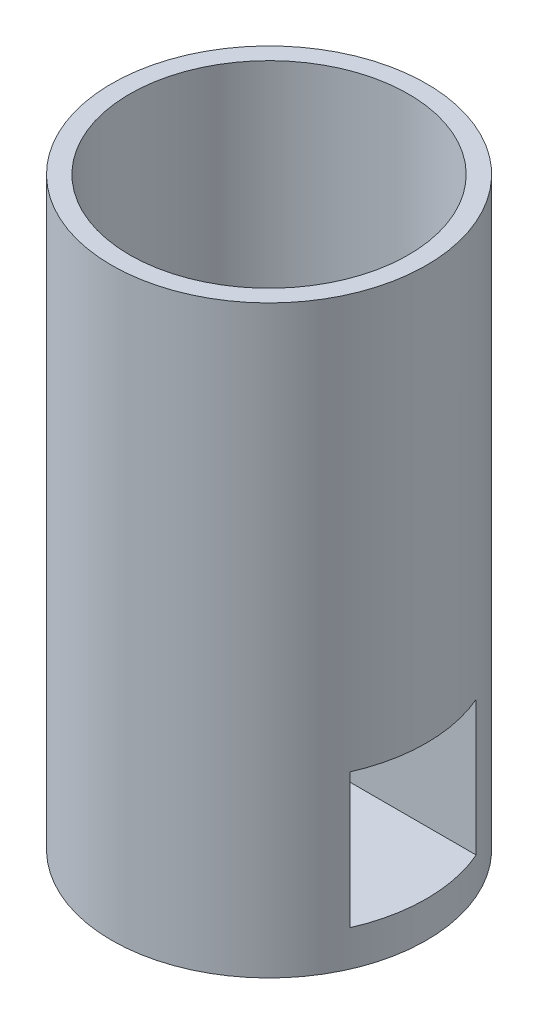
SolidWorks part; units mm, degrees
ref_plane "Front Plane" through (0, 0, 0) normal (0, 0, 1) x (1, 0, 0)
ref_plane "Top Plane" through (0, 0, 0) normal (0, 1, 0) x (1, 0, 0)
ref_plane "Right Plane" through (0, 0, 0) normal (1, 0, 0) x (0, 0, -1)
sketch "Sketch1" plane through (0, 0, 0) normal (0, 1, 0) x (1, 0, 0)
  line L1 (-9.2182, 6.0273) -> (15.7818, 6.0273)
  line L2 (-9.2182, 6.0273) -> (-9.2182, -9.9727)
  line L3 (-9.2182, -9.9727) -> (15.7818, -9.9727)
  line L4 (15.7818, 6.0273) -> (15.7818, -9.9727)
  dimension "D1" = 16
  dimension "D2" = 25
extrude "Boss-Extrude1" add sketch "Sketch1" along normal blind 20
sketch "Sketch6" plane through (0, 0, 0) normal (0, 1, 0) x (1, 0, 0)
  circle A0 centre (3.8725, -1.9531) radius 17.5
extrude "Boss-Extrude4" add sketch "Sketch6" along normal blind 65
sketch "Sketch2" plane through (-9.2182, 0, 0) normal (-1, 0, 0) x (0, 0, 1)
  line L0 (-6.0273, 20) -> (-6.0273, 0) construction
  line L1 (-5.0273, 19) -> (8.9727, 19)
  line L2 (-5.0273, 19) -> (-5.0273, 4)
  line L3 (-5.0273, 4) -> (8.9727, 4)
  line L4 (8.9727, 19) -> (8.9727, 4)
  line L5 (9.9727, 20) -> (9.9727, 0) construction
  line L6 (-6.0273, 20) -> (9.9727, 20) construction
  dimension "D1" = 1
  dimension "D2" = 1
  dimension "D3" = 1
  dimension "D4" = 15
extrude "Cut-Extrude1" cut sketch "Sketch2" against normal blind 40 and the other way blind 65
sketch "Sketch3" plane through (0, 0, 0) normal (0, -1, 0) x (-1, 0, 0)
  line L0 (-15.7818, -9.9727) -> (-15.7818, 6.0273) construction
  line L1 (9.2182, -9.9727) -> (-15.7818, -9.9727) construction
  line L2 (-15.7818, 6.0273) -> (9.2182, 6.0273) construction
  circle A0 centre (-9.7818, -1.9727) radius 1
  circle A1 centre (0.2182, -1.9727) radius 1
  dimension "D6" = 2
  dimension "D7" = 2
  dimension "D1" = 6
  dimension "D2" = 16
  dimension "D3" = 16
  dimension "D4" = 8
  dimension "D5" = 8
extrude "Cut-Extrude2" cut sketch "Sketch3" against normal blind 10
sketch "Sketch7" plane through (0, 65, 0) normal (0, 1, 0) x (1, 0, 0)
  circle A0 centre (3.8725, -1.9531) radius 15.5
  circle A1 centre (3.8725, -1.9531) radius 17.5 construction
  dimension "D1" = 0
  dimension "D2" = 2
extrude "Cut-Extrude3" cut sketch "Sketch7" against normal blind 30
